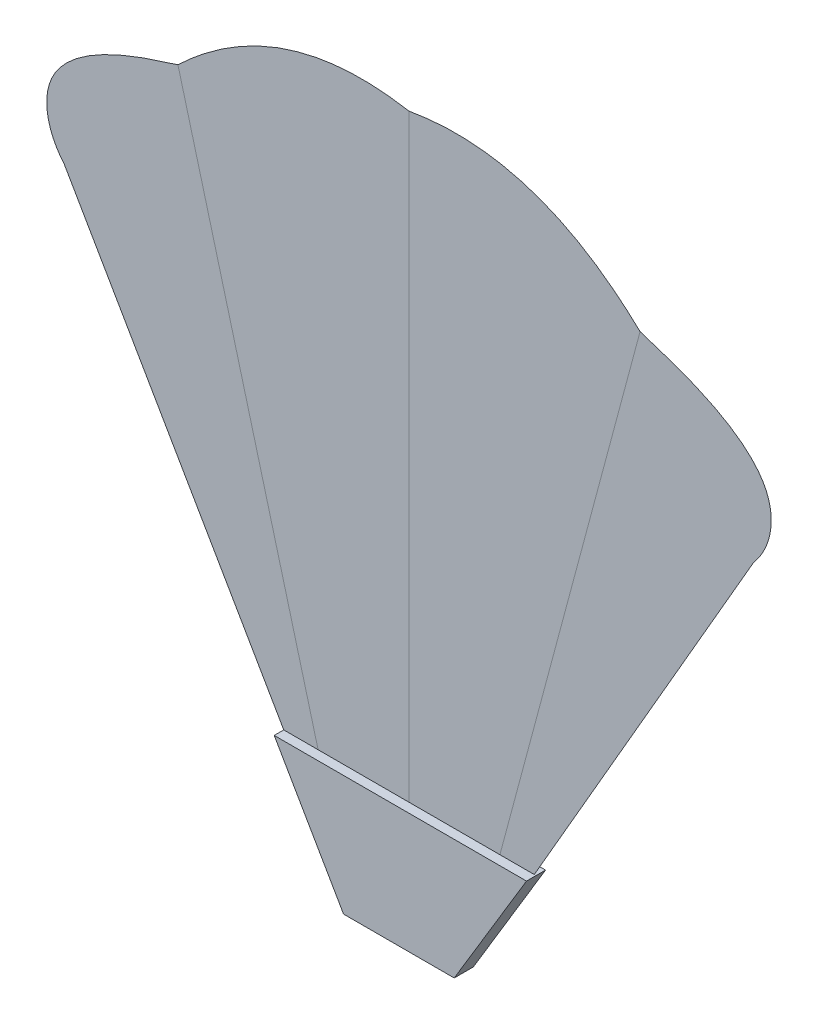
SolidWorks part; units mm, degrees
ref_plane "Front Plane" through (0, 0, 0) normal (0, 0, 1) x (1, 0, 0)
ref_plane "Top Plane" through (0, 0, 0) normal (0, 1, 0) x (1, 0, 0)
ref_plane "Right Plane" through (0, 0, 0) normal (1, 0, 0) x (0, 0, -1)
sketch "Sketch3" plane through (0, 0, 0) normal (0, 0, 1) x (1, 0, 0)
  line L0 (0, 241.2176) -> (0, -472.7159) construction
  line L1 (-30, -401.1052) -> (-96.9873, -151.1052)
  line L2 (0, -401.1052) -> (-30, -401.1052)
  line L3 (0, -119.4533) -> (0, -401.1052)
  spline S0 degree 2 poles (-96.9873, -151.1052) (-53.82, -109.9041) (0, -119.4533) knots 0 0 0 1 1 1
  dimension "D1" = 250
  dimension "D2" = 15
  dimension "D3" = 30
surface "Surface-Fill2" sketch "Sketch3"
sketch "Sketch4" plane through (0, 0, 0) normal (0, 0, 1) x (1, 0, 0)
  line L0 (-35, -401.1052) -> (-144.6966, -211.1052)
  line L1 (0, -401.1052) -> (0, -119.4533) construction
  line L2 (-30, -401.1052) -> (0, -401.1052) construction
  line L3 (-35, -401.1052) -> (-30, -401.1052)
  line L4 (-30, -401.1052) -> (-96.9873, -151.1052)
  spline S0 degree 3 poles (-144.6966, -211.1052) (-151.5035, -203.1932) (-158.4714, -169.561) (-111.9034, -155.8045) (-96.9873, -151.1052) knots 0 0 0 0 0.29638 1 1 1 1
  dimension "D1" = 30
  dimension "D2" = 35
  dimension "D3" = 0
  dimension "D4" = 190
surface "Surface-Fill3" sketch "Sketch4"
mirror "Mirror1" about plane through (0, 0, 0) normal (1, 0, 0)
sketch "Sketch5" plane through (0, 0, 0) normal (0, 0, 1) x (1, 0, 0)
  line L0 (-144.6966, -211.1052) -> (-35, -401.1052) construction
  line L1 (-52.571, -370.6713) -> (53.3175, -370.6713)
  line L5 (-52.571, -370.6713) -> (-23.4713, -421.0736)
  line L6 (-23.4713, -421.0736) -> (22.9815, -421.0736)
  line L7 (22.9815, -421.0736) -> (53.3175, -370.6713)
extrude "Boss-Extrude1" add sketch "Sketch5" along normal mid plane 8
sketch "Sketch6" plane through (0, -421.0736, 0) normal (0, -1, 0) x (1, 0, 0)
  circle A0 centre (0, 0) radius 1.75
  dimension "D1" = 3.5
extrude "Cut-Extrude1" cut sketch "Sketch6" against normal blind 5
